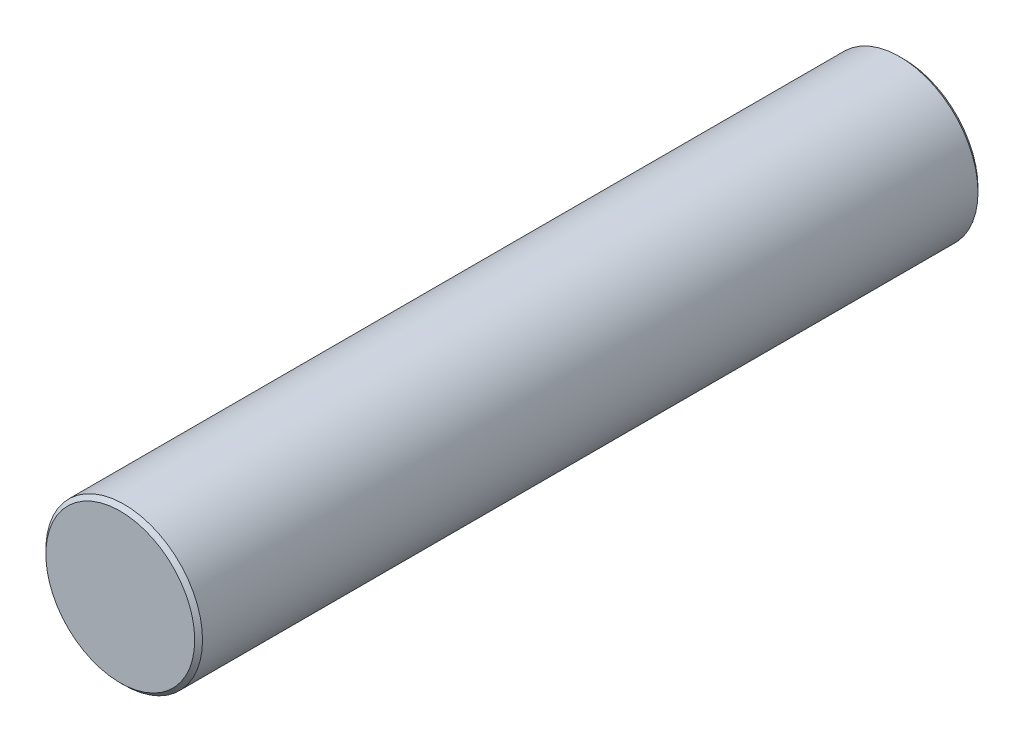
SolidWorks part; units mm, degrees
ref_plane "前视基准面" through (0, 0, 0) normal (0, 0, 1) x (1, 0, 0)
ref_plane "上视基准面" through (0, 0, 0) normal (0, 1, 0) x (1, 0, 0)
ref_plane "右视基准面" through (0, 0, 0) normal (1, 0, 0) x (0, 0, -1)
sketch "草图1" plane through (0, 0, 0) normal (0, 0, 1) x (1, 0, 0)
  circle A0 centre (0, 0) radius 2
  dimension "D1" = 4
extrude "凸台-拉伸1" add sketch "草图1" along normal blind 20
sketch "草图2" plane through (0, 0, 0) normal (0, 0, -1) x (-1, 0, 0)
  circle A0 centre (0, 0) radius 1
  dimension "D1" = 2
extrude "切除-拉伸1" cut sketch "草图2" against normal blind 11
chamfer "倒角1" distance 0.1 angle 45 2 edges at (2, 0, 20) (2, 0, 0)
